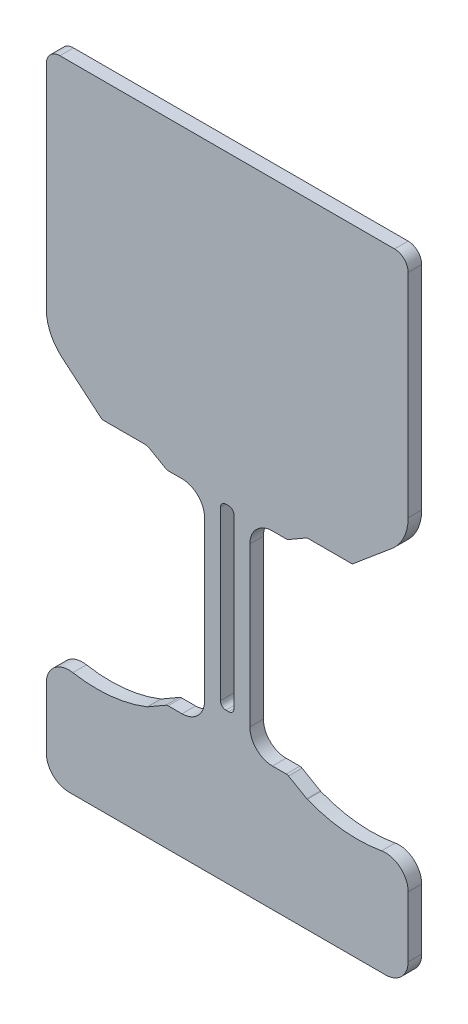
SolidWorks part; units mm, degrees
ref_plane "Plano frontal" through (0, 0, 0) normal (0, 0, 1) x (1, 0, 0)
ref_plane "Plano superior" through (0, 0, 0) normal (0, 1, 0) x (1, 0, 0)
ref_plane "Plano direito" through (0, 0, 0) normal (1, 0, 0) x (0, 0, -1)
sketch "Esboço2" plane through (0, 0, 0) normal (0, 0, 1) x (1, 0, 0)
  line L0 (31.4274, 25.0613) -> (22.6538, 17.6994)
  line L1 (0, 10.1994) -> (0, -24.8006)
  line L2 (34.9995, 77.6994) -> (34.9995, 32.7217)
  line L3 (-5, 57.1507) -> (-5, -43.7684) construction
  line L4 (22.6538, 17.6994) -> (12.9218, 17.6994)
  line L5 (12.4218, 17.5654) -> (8.5557, 15.3334)
  line L6 (8.0557, 15.1994) -> (5, 15.1994)
  line L7 (12.5873, -32.2644) -> (8.5519, -29.9346)
  line L8 (8.0519, -29.8006) -> (5, -29.8006)
  line L9 (30, -57.3006) -> (-40, -57.3006)
  line L10 (29.9995, 82.6994) -> (-39.9995, 82.6994)
  line L11 (-33.825, -32.3006) -> (-45, -32.3006) construction
  line L12 (-33.825, -32.3006) -> (-33.825, -35.3006) construction
  line L13 (12.65, -32.3006) -> (23.825, -32.3006) construction
  line L14 (23.825, -32.3006) -> (23.825, -35.3006) construction
  line L15 (23.825, -32.3006) -> (35, -32.3006) construction
  line L16 (35, -38.9038) -> (35, -52.3006)
  line L17 (-22.65, -32.3006) -> (-33.825, -32.3006) construction
  line L18 (-45, -38.9038) -> (-45, -52.3006)
  line L19 (-18.0519, -29.8006) -> (-15, -29.8006)
  line L20 (-22.5873, -32.2644) -> (-18.5519, -29.9346)
  line L21 (-18.0557, 15.1994) -> (-15, 15.1994)
  line L22 (-22.4218, 17.5654) -> (-18.5557, 15.3334)
  line L23 (-32.6538, 17.6994) -> (-22.9218, 17.6994)
  line L24 (-44.9995, 77.6994) -> (-44.9995, 32.7217)
  line L25 (-10, 10.1994) -> (-10, -24.8006)
  line L26 (-41.4274, 25.0613) -> (-32.6538, 17.6994)
  line L27 (34.9995, 77.6994) -> (34.9995, 79.6994)
  line L28 (31.9995, 82.6994) -> (29.9995, 82.6994)
  line L29 (-39.9995, 82.6994) -> (-41.9995, 82.6994)
  line L30 (-44.9995, 79.6994) -> (-44.9995, 77.6994)
  arc A0 (31.4274, 25.0613) -> (34.9995, 32.7217) centre (24.9995, 32.7217) ccw
  arc A1 (34.9995, 79.6994) -> (31.9995, 82.6994) centre (31.9995, 79.6994) ccw
  arc A2 (5, 15.1994) -> (0, 10.1994) centre (5, 10.1994) ccw
  arc A3 (5, -29.8006) -> (0, -24.8006) centre (5, -24.8006) cw
  arc A4 (12.7184, -32.3278) -> (29.1206, -33.9818) centre (23.825, -4.3405) ccw
  arc A5 (35, -52.3006) -> (30, -57.3006) centre (30, -52.3006) cw
  arc A6 (29.1206, -33.9818) -> (35, -38.9038) centre (30, -38.9038) cw
  arc A7 (8.5519, -29.9346) -> (8.0519, -29.8006) centre (8.0519, -30.8006) ccw
  arc A8 (12.5873, -32.2644) -> (12.7184, -32.3278) centre (13.0873, -31.3984) ccw
  arc A9 (8.5557, 15.3334) -> (8.0557, 15.1994) centre (8.0557, 16.1994) cw
  arc A10 (12.9218, 17.6994) -> (12.4218, 17.5654) centre (12.9218, 16.6994) ccw
  arc A11 (-22.9218, 17.6994) -> (-22.4218, 17.5654) centre (-22.9218, 16.6994) cw
  arc A12 (-18.5557, 15.3334) -> (-18.0557, 15.1994) centre (-18.0557, 16.1994) ccw
  arc A13 (-22.5873, -32.2644) -> (-22.7184, -32.3278) centre (-23.0873, -31.3984) cw
  arc A14 (-18.5519, -29.9346) -> (-18.0519, -29.8006) centre (-18.0519, -30.8006) cw
  arc A15 (-39.1206, -33.9818) -> (-45, -38.9038) centre (-40, -38.9038) ccw
  arc A16 (-45, -52.3006) -> (-40, -57.3006) centre (-40, -52.3006) ccw
  arc A17 (-22.7184, -32.3278) -> (-39.1206, -33.9818) centre (-33.825, -4.3405) cw
  arc A18 (-15, -29.8006) -> (-10, -24.8006) centre (-15, -24.8006) ccw
  arc A19 (-15, 15.1994) -> (-10, 10.1994) centre (-15, 10.1994) cw
  arc A20 (-41.9995, 82.6994) -> (-44.9995, 79.6994) centre (-41.9995, 79.6994) ccw
  arc A21 (-41.4274, 25.0613) -> (-44.9995, 32.7217) centre (-34.9995, 32.7217) cw
  point P31 (35, -57.3006)
  point P41 (-5, -57.3006)
  point P44 (-5, -57.3006)
  point P46 (-5, -57.3006)
  point P48 (-5, 82.6994)
  point P80 (-5, 82.6994)
  point P81 (-45, -57.3006)
  point P82 (20.8041, -34.2992)
  dimension "D1" = 10
  dimension "D9" = 25
  dimension "D10" = 5
  dimension "D11" = 5
  dimension "D12" = 1
  dimension "D16" = 3
  dimension "D2" = 60
  dimension "D3" = 50
  dimension "D4" = 40
  dimension "D5" = 39.9995
  dimension "D6" = 5
  dimension "D7" = 150
  dimension "D8" = 150
  dimension "D13" = 2.5
  dimension "D14" = 4.4986
  dimension "D15" = 35
extrude "Ressalto-extrusão4" add sketch "Esboço2" along normal blind 3 contours L10 L29 A20 L30 L24 A21 L26 L23 A11 L22 A12 L21 A19 L25 A18 L19 A14 L20 A13 A17 A15 L18 A16 L9 A5 L16 A6 A4 A8 L7 A7 L8 A3 L1 A2 L6 A9 L5 A10 L4 L0 A0 L2 L27 A1 L28
sketch "Esboço3" plane through (0, 0, 0) normal (0, 0, -1) x (-1, 0, 0)
  line L0 (0, 10.1994) -> (0, -24.8006) construction
  line L1 (4.7, 15.1994) -> (5.3, 15.1994)
  line L2 (3.5, 13.9994) -> (3.5, -23.0506)
  line L3 (4.7, -24.2506) -> (5.3, -24.2506)
  line L4 (6.5, 13.9994) -> (6.5, -23.0506)
  line L5 (10, 10.1994) -> (10, -24.8006) construction
  line L6 (18.0557, 15.1994) -> (15, 15.1994) construction
  arc A0 (5.3, 15.1994) -> (6.5, 13.9994) centre (5.3, 13.9994) cw
  arc A1 (4.7, 15.1994) -> (3.5, 13.9994) centre (4.7, 13.9994) ccw
  arc A2 (5.3, -24.2506) -> (6.5, -23.0506) centre (5.3, -23.0506) ccw
  arc A3 (3.5, -23.0506) -> (4.7, -24.2506) centre (4.7, -23.0506) ccw
  point P12 (6.5, 15.1994)
  point P17 (6.5, -24.2506)
  dimension "D6" = 1.2
  dimension "D1" = 3
  dimension "D2" = 3.5
  dimension "D3" = 3.5
  dimension "D4" = 39.45
  dimension "D5" = 0
extrude "Corte-extrusão1" cut sketch "Esboço3" against normal blind 3
